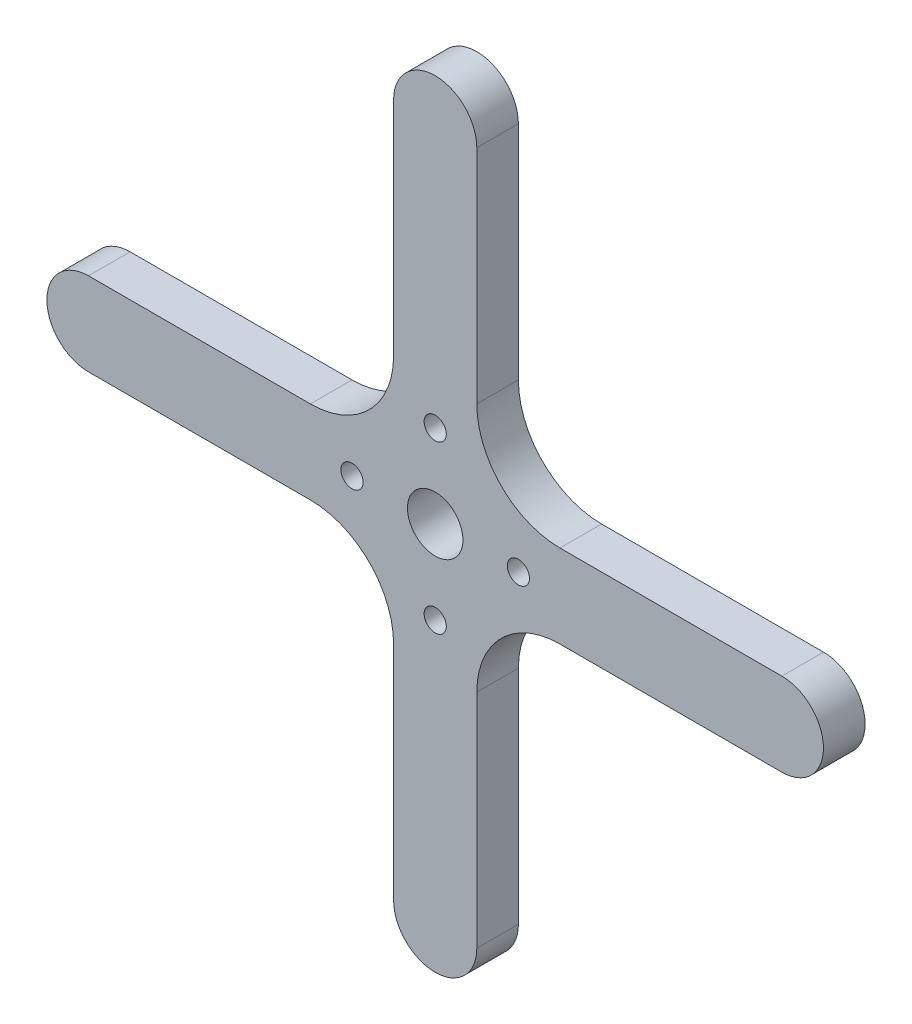
SolidWorks part; units mm, degrees
ref_plane "Front Plane" through (0, 0, 0) normal (0, 0, 1) x (1, 0, 0)
ref_plane "Top Plane" through (0, 0, 0) normal (0, 1, 0) x (1, 0, 0)
ref_plane "Right Plane" through (0, 0, 0) normal (1, 0, 0) x (0, 0, -1)
sketch "Sketch1" plane through (0, 0, 0) normal (0, 0, 1) x (1, 0, 0)
  line L0 (6, 0) -> (-6, 0)
  line L1 (25, 0) -> (-25, 0) construction
  line L2 (25, -3) -> (-25, -3)
  line L3 (25, 3) -> (-25, 3)
  line L4 (0, -25) -> (0, 25) construction
  line L5 (-3, -25) -> (-3, 25)
  line L6 (3, -25) -> (3, 25)
  line L7 (0, 6) -> (0, -6)
  circle A0 centre (-6, 0) radius 0.8
  circle A1 centre (6, 0) radius 0.8
  arc A2 (25, -3) -> (25, 3) centre (25, 0) ccw
  arc A3 (-25, 3) -> (-25, -3) centre (-25, 0) ccw
  arc A4 (-3, -25) -> (3, -25) centre (0, -25) ccw
  arc A5 (3, 25) -> (-3, 25) centre (0, 25) ccw
  circle A6 centre (0, 6) radius 0.8
  circle A7 centre (0, -6) radius 0.8
  point P4 (0, 0)
  point P9 (0, 0)
  point P15 (0, 0)
  point P24 (0, 8.7103)
  point P25 (0, 0)
  dimension "D1" = 1.6
  dimension "D3" = 1.6
  dimension "D5" = 3
  dimension "D7" = 3
  dimension "D8" = 1.6
  dimension "D9" = 1.6
  dimension "D2" = 12
  dimension "D4" = 50
  dimension "D6" = 50
  dimension "D10" = 12
extrude "Boss-Extrude1" add sketch "Sketch1" along normal blind 3
fillet "Fillet1" radius 6 4 edges at (-3, 3, 1.5) (-3, -3, 1.5) (3, -3, 1.5) (3, 3, 1.5)
sketch "Sketch2" plane through (0, 0, 3) normal (0, 0, 1) x (1, 0, 0)
  circle A0 centre (0, 0) radius 2
  dimension "D1" = 4
extrude "Cut-Extrude1" cut sketch "Sketch2" against normal blind 3
